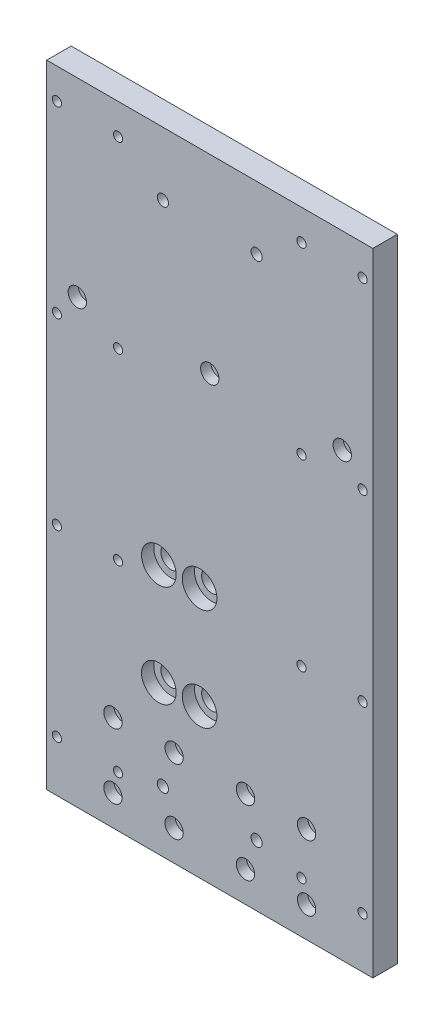
SolidWorks part; units mm, degrees
ref_plane "Plan de face" through (0, 0, 0) normal (0, 0, 1) x (1, 0, 0)
ref_plane "Plan de dessus" through (0, 0, 0) normal (0, 1, 0) x (1, 0, 0)
ref_plane "Plan de droite" through (0, 0, 0) normal (1, 0, 0) x (0, 0, -1)
sketch "Esquisse1" plane through (0, 0, 0) normal (0, 0, 1) x (1, 0, 0)
  line L0 (80, 310) -> (80, 0) construction
  line L1 (0, 0) -> (160, 0)
  line L2 (0, 0) -> (0, 310)
  line L3 (0, 310) -> (160, 310)
  line L4 (160, 0) -> (160, 310)
  line L5 (160, 155) -> (0, 155) construction
  circle A0 centre (97.5, 15) radius 2.5
  circle A1 centre (127.5, 15) radius 2.5
  circle A2 centre (97.5, 47) radius 2.5
  circle A3 centre (127.5, 47) radius 2.5
  circle A4 centre (62.5, 47) radius 2.5
  circle A5 centre (32.5, 47) radius 2.5
  circle A6 centre (32.5, 15) radius 2.5
  circle A7 centre (62.5, 15) radius 2.5
  circle A8 centre (57, 30) radius 2.75
  circle A9 centre (103, 30) radius 2.75
  circle A10 centre (57, 279) radius 2.75
  circle A11 centre (103, 279) radius 2.75
  circle A12 centre (15, 216.85) radius 2.25
  circle A13 centre (80, 216.85) radius 2.25
  circle A14 centre (145, 216.85) radius 2.25
  dimension "D7" = 5
  dimension "D10" = 23
  dimension "D4" = 5
  dimension "D9" = 5.5
  dimension "D11" = 30
  dimension "D13" = 4.5
  dimension "D14" = 15
  dimension "D15" = 93.15
  dimension "D1" = 310
  dimension "D2" = 160
  dimension "D3" = 17.5
  dimension "D5" = 15
  dimension "D6" = 30
  dimension "D8" = 2
  dimension "D12" = 2
  dimension "D16" = 3
extrude "Boss.-Extru.1" add sketch "Esquisse1" along normal blind 12
sketch "Esquisse2" plane through (0, 0, 12) normal (0, 0, 1) x (1, 0, 0)
  line L0 (80, 0) -> (80, 59.8203) construction
  line L1 (0, 0) -> (160, 0) construction
  circle A0 centre (32.5, 47) radius 4.5
  circle A1 centre (32.5, 15) radius 4.5
  circle A2 centre (62.5, 15) radius 4.5
  circle A3 centre (62.5, 47) radius 4.5
  circle A4 centre (127.5, 15) radius 4.5
  circle A5 centre (97.5, 15) radius 4.5
  circle A6 centre (97.5, 47) radius 4.5
  circle A7 centre (127.5, 47) radius 4.5
  circle A8 centre (15, 216.85) radius 4.5
  circle A9 centre (80, 216.85) radius 4.5
  circle A10 centre (145, 216.85) radius 4.5
  dimension "D1" = 9
  dimension "D2" = 9
  dimension "D3" = 9
  dimension "D4" = 9
  dimension "D5" = 9
  dimension "D6" = 9
  dimension "D7" = 9
extrude "Enlèv. mat.-Extru.1" cut sketch "Esquisse2" against normal blind 5
sketch "Esquisse3" plane through (0, 0, 12) normal (0, 0, 1) x (1, 0, 0)
  line L0 (80, 0) -> (80, 343.116) construction
  line L1 (0, 0) -> (160, 0) construction
  line L2 (160, 0) -> (160, 310) construction
  circle A0 centre (155, 25) radius 2.25
  circle A1 centre (125, 25) radius 2.25
  circle A2 centre (125, 115) radius 2.25
  circle A3 centre (125, 205) radius 2.25
  circle A4 centre (125, 295) radius 2.25
  circle A5 centre (155, 115) radius 2.25
  circle A6 centre (155, 205) radius 2.25
  circle A7 centre (155, 295) radius 2.25
  circle A8 centre (5, 295) radius 2.25
  circle A9 centre (35, 295) radius 2.25
  circle A10 centre (5, 205) radius 2.25
  circle A11 centre (35, 205) radius 2.25
  circle A12 centre (35, 115) radius 2.25
  circle A13 centre (5, 115) radius 2.25
  circle A14 centre (35, 25) radius 2.25
  circle A15 centre (5, 25) radius 2.25
  dimension "D1" = 4.5
  dimension "D2" = 5
  dimension "D3" = 25
  dimension "D4" = 2
  dimension "D5" = 4
extrude "Enlèv. mat.-Extru.2" cut sketch "Esquisse3" against normal up to next
sketch "Esquisse4" plane through (0, 0, 12) normal (0, 0, 1) x (1, 0, 0)
  line L0 (0, 310) -> (0, 0) construction
  line L1 (0, 0) -> (160, 0) construction
  circle A0 centre (55, 73) radius 5
  circle A1 centre (75, 73) radius 5
  circle A2 centre (75, 123) radius 5
  circle A3 centre (55, 123) radius 5
  dimension "D1" = 10
  dimension "D2" = 55
  dimension "D3" = 73
  dimension "D4" = 2
  dimension "D5" = 2
extrude "Enlèv. mat.-Extru.3" cut sketch "Esquisse4" against normal up to next
sketch "Esquisse5" plane through (0, 0, 12) normal (0, 0, 1) x (1, 0, 0)
  circle A0 centre (55, 123) radius 8.5
  circle A1 centre (75, 123) radius 8.5
  circle A2 centre (75, 73) radius 8.5
  circle A3 centre (55, 73) radius 8.5
  dimension "D1" = 17
  dimension "D2" = 17
  dimension "D3" = 17
  dimension "D4" = 17
extrude "Enlèv. mat.-Extru.4" cut sketch "Esquisse5" against normal blind 6
